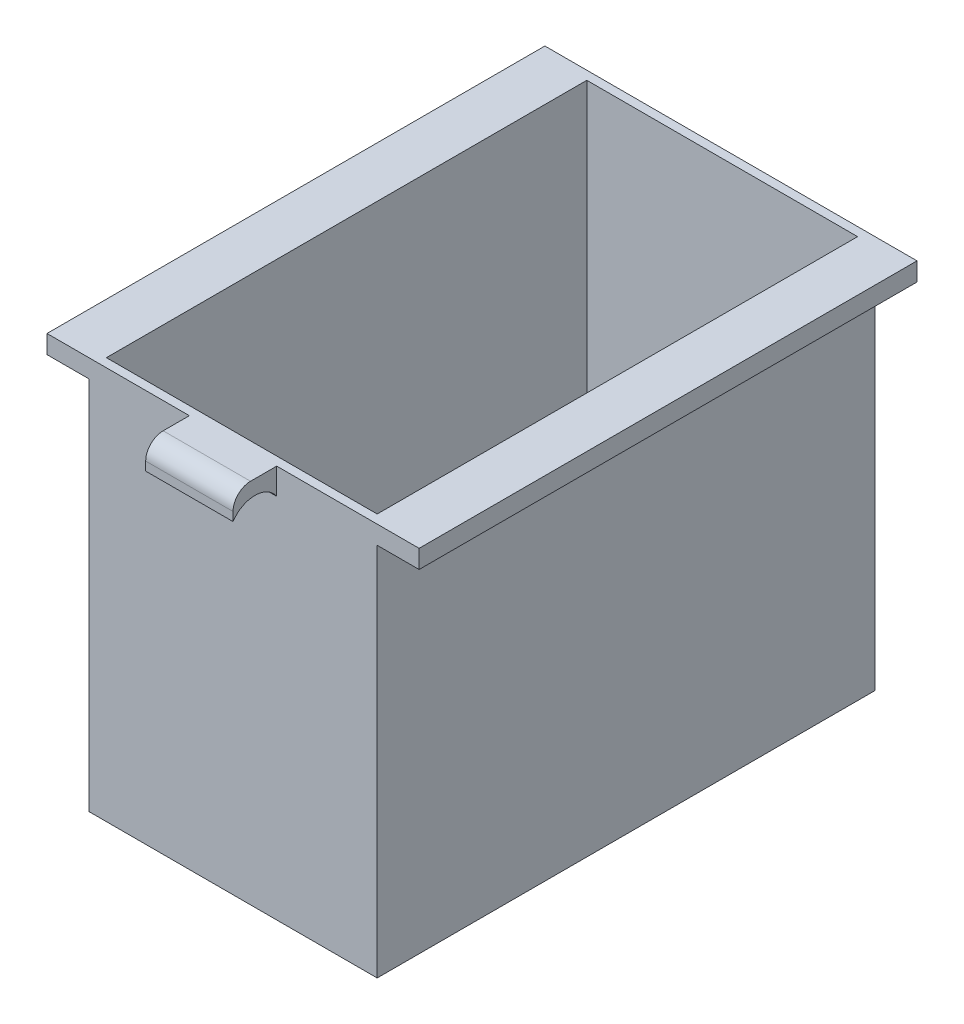
SolidWorks part; units mm, degrees
ref_plane "Front Plane" through (0, 0, 0) normal (0, 0, 1) x (1, 0, 0)
ref_plane "Top Plane" through (0, 0, 0) normal (0, 1, 0) x (1, 0, 0)
ref_plane "Right Plane" through (0, 0, 0) normal (1, 0, 0) x (0, 0, -1)
sketch "Sketch1" plane through (0, 0, 0) normal (0, 1, 0) x (1, 0, 0)
  line L1 (16.5, -28.5) -> (-16.5, -28.5)
  line L2 (16.5, -28.5) -> (16.5, 28.5)
  line L3 (16.5, 28.5) -> (-16.5, 28.5)
  line L4 (-16.5, -28.5) -> (-16.5, 28.5)
  line L5 (16.5, -28.5) -> (-16.5, 28.5) construction
  line L6 (16.5, 28.5) -> (-16.5, -28.5) construction
  point P0 (0, 0)
  dimension "D1" = 57
  dimension "D2" = 33
extrude "Boss-Extrude1" add sketch "Sketch1" along normal blind 45
shell "Shell1" thickness 1
sketch "Sketch3" plane through (-16.5, 0, 0) normal (-1, 0, 0) x (0, 0, 1)
  line L0 (28.5, 45) -> (28.5, 0) construction
  line L1 (-28.5, 45) -> (28.5, 45)
  line L2 (-28.5, 45) -> (-28.5, 42.9)
  line L3 (-28.5, 42.9) -> (28.5, 42.9)
  line L4 (28.5, 45) -> (28.5, 42.9)
  dimension "D1" = 2.1
extrude "Boss-Extrude2" add sketch "Sketch3" along normal blind 4.8
mirror "Mirror1" about plane through (0, 0, 0) normal (1, 0, 0) of "Boss-Extrude2"
sketch "Sketch4" plane through (0, 0, 28.5) normal (0, 0, 1) x (1, 0, 0)
  line L0 (-21.3, 45) -> (21.3, 45) construction
  line L1 (-5, 45) -> (5, 45)
  line L2 (-5, 45) -> (-5, 42)
  line L3 (-5, 42) -> (5, 42)
  line L4 (5, 45) -> (5, 42)
  dimension "D1" = 10
  dimension "D2" = 3
  dimension "D3" = 5
extrude "Boss-Extrude3" add sketch "Sketch4" along normal blind 5
sketch "Sketch5" plane through (-5, 0, 0) normal (-1, 0, 0) x (0, 0, 1)
  line L0 (28.5, 42) -> (33.5, 42)
  arc A0 (28.5, 42) -> (33.5, 42) centre (31, 40.3417) cw
  dimension "D1" = 3
extrude "Cut-Extrude1" cut sketch "Sketch5" against normal blind 10
fillet "Fillet2" radius 2 1 edges at (0, 45, 33.5)
